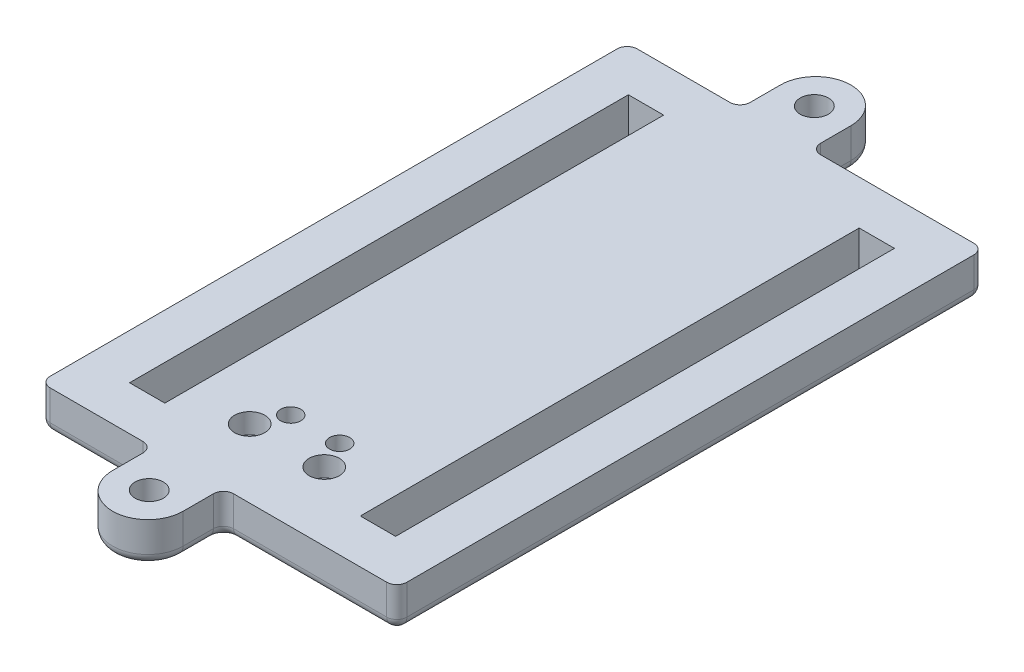
SolidWorks part; units mm, degrees
ref_plane "Front Plane" through (0, 0, 0) normal (0, 0, 1) x (1, 0, 0)
ref_plane "Top Plane" through (0, 0, 0) normal (0, 1, 0) x (1, 0, 0)
ref_plane "Right Plane" through (0, 0, 0) normal (1, 0, 0) x (0, 0, -1)
sketch "Sketch1" plane through (0, 0, 0) normal (0, 1, 0) x (1, 0, 0)
  line L0 (0, 29.13) -> (0, -29.13) construction
  line L1 (-17.7, 29.13) -> (17.7, 29.13)
  line L2 (-17.7, 29.13) -> (-17.7, -29.13)
  line L3 (-17.7, -29.13) -> (17.7, -29.13)
  line L4 (17.7, 29.13) -> (17.7, -29.13)
  line L5 (-17.7, 29.13) -> (17.7, -29.13) construction
  line L6 (-17.7, -29.13) -> (17.7, 29.13) construction
  line L7 (-13.2, 24.75) -> (-9.7, 24.75)
  line L8 (-13.2, 24.75) -> (-13.2, -24.75)
  line L9 (-13.2, -24.75) -> (-9.7, -24.75)
  line L10 (-9.7, 24.75) -> (-9.7, -24.75)
  line L11 (13.2, -24.75) -> (9.7, -24.75)
  line L12 (9.7, 24.75) -> (9.7, -24.75)
  line L13 (13.2, 24.75) -> (9.7, 24.75)
  line L14 (13.2, 24.75) -> (13.2, -24.75)
  line L15 (-17.7, 0) -> (17.7, 0) construction
  line L16 (0, -24.13) -> (0, 24.13) construction
  line L17 (-12.7, -24.13) -> (12.7, -24.13) construction
  line L18 (-12.7, -24.13) -> (-12.7, 24.13) construction
  line L19 (-12.7, 24.13) -> (12.7, 24.13) construction
  line L20 (12.7, -24.13) -> (12.7, 24.13) construction
  point P0 (0, 0)
  point P10 (-9.7, 0)
  point P11 (-11.45, -24.75)
  point P26 (0, 0)
  dimension "D6" = 25.4
  dimension "D1" = 35.4
  dimension "D2" = 58.26
  dimension "D3" = 3.5
  dimension "D4" = 49.5
  dimension "D5" = 11.45
  dimension "D7" = 48.26
extrude "Base" add sketch "Sketch1" along normal blind 4
sketch "Sketch2" plane through (0, 0, 0) normal (0, 1, 0) x (1, 0, 0)
  line L0 (0, 0) -> (0, 29.13) construction
  line L1 (17.7, 29.13) -> (-17.7, 29.13) construction
  line L2 (-6.5, 29.13) -> (0.5, 29.13)
  line L3 (-6.5, 29.13) -> (-6.5, 33.13)
  line L4 (0.5, 29.13) -> (0.5, 33.13)
  line L5 (-17.7, 0) -> (17.7, 0) construction
  line L6 (-17.7, 29.13) -> (-17.7, -29.13) construction
  line L7 (17.7, -29.13) -> (17.7, 29.13) construction
  line L8 (-6.5, -29.13) -> (-6.5, -33.13)
  line L9 (-6.5, -29.13) -> (0.5, -29.13)
  line L10 (0.5, -29.13) -> (0.5, -33.13)
  circle A0 centre (-3, 33) radius 1.4
  arc A2 (-6.5, 33.13) -> (0.5, 33.13) centre (-3, 33.13) cw
  arc A3 (-6.5, -33.13) -> (0.5, -33.13) centre (-3, -33.13) ccw
  circle A4 centre (-3, -33) radius 1.4
  point P25 (0, 0)
  point P26 (0, 0)
  point P27 (-3, 29.13)
  dimension "D1" = 33
  dimension "D2" = 2.8
  dimension "D5" = 3
  dimension "D3" = 7
  dimension "D4" = 4
extrude "Mounting Ends" add sketch "Sketch2" along normal up to surface (4 mm away) up to face at (0, 4, 0)
sketch "Sketch3" plane through (0, 0, 0) normal (0, -1, 0) x (1, 0, 0)
  line L0 (0, 29.13) -> (0, -29.13) construction
  line L1 (-12.7, -24.13) -> (12.7, -24.13) construction
  line L2 (-12.7, -24.13) -> (-12.7, 24.13) construction
  line L3 (-12.7, 24.13) -> (12.7, 24.13) construction
  line L4 (12.7, -24.13) -> (12.7, 24.13) construction
  line L5 (-6.5, -29.13) -> (-17.7, -29.13) construction
  line L6 (-17.7, 29.13) -> (-6.5, 29.13) construction
  circle A2 centre (-3.7, 22.33) radius 1.5
  circle A3 centre (-2.43, 19.53) radius 1
  circle A4 centre (2.43, 19.53) radius 1
  circle A5 centre (3.7, 22.33) radius 1.5
  point P2 (3, -28.0347)
  point P5 (0, 0)
  point P11 (-12.7, 0)
  point P12 (0, 24.13)
  point P22 (0, 0)
  dimension "D3" = 9
  dimension "D5" = 3
  dimension "D6" = 10.27
  dimension "D8" = 2
  dimension "D1" = 48.26
  dimension "D2" = 25.4
  dimension "D4" = 1.8
  dimension "D7" = 4.6
extrude "Top Cutouts" cut sketch "Sketch3" along normal blind 2 from surface at -4 starting at face at (-2, 4, 0)
fillet "1mm Edge Fillets" radius 1 20 edges at (-12.1, 0, 29.13) (9.1, 0, -29.13) (-6.5, 0, 31.13) (0.5, 0, -31.13) (-3, 0, 36.63) (-3, 0, -36.63) (0.5, 0, 31.13) (-6.5, 0, -31.13) (9.1, 0, 29.13) (17.7, 0, 0) (-12.1, 0, -29.13) (-17.7, 0, 0) (-17.7, 2, -29.13) (-6.5, 2, -29.13) (0.5, 2, -29.13) (17.7, 2, -29.13) (0.5, 2, 29.13) (-6.5, 2, 29.13) (17.7, 2, 29.13) (-17.7, 2, 29.13)
